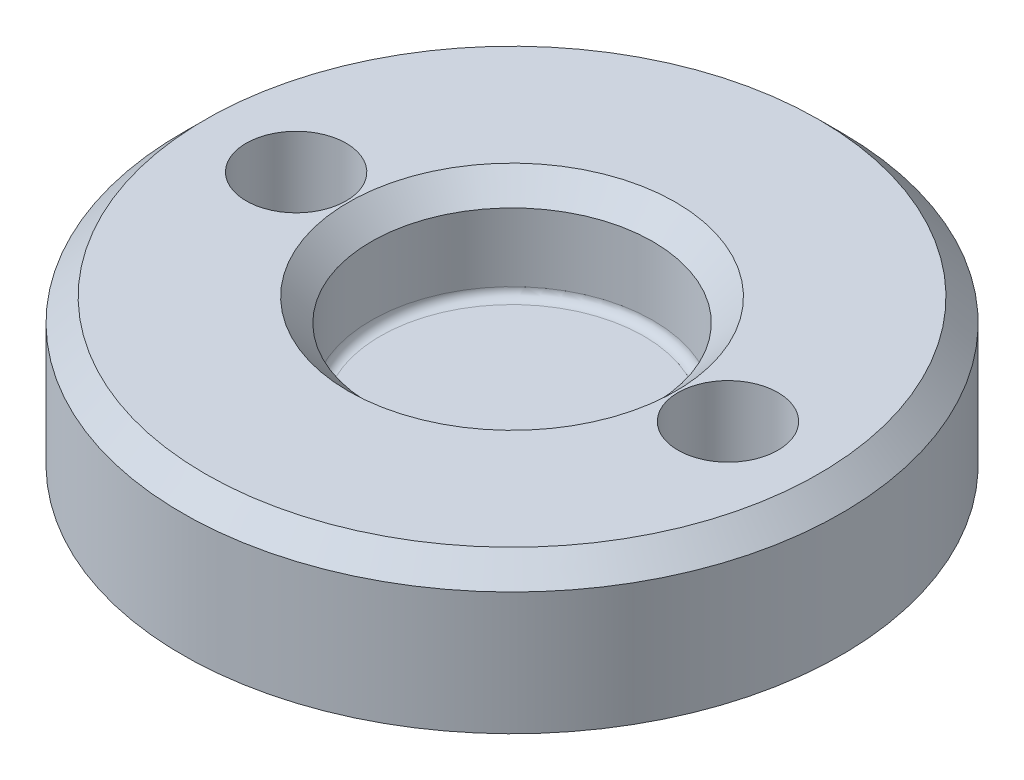
SolidWorks part; units mm, degrees
material "Brass"
ref_plane "Front Plane" through (0, 0, 0) normal (0, 0, 1) x (1, 0, 0)
ref_plane "Top Plane" through (0, 0, 0) normal (0, 1, 0) x (1, 0, 0)
ref_plane "Right Plane" through (0, 0, 0) normal (1, 0, 0) x (0, 0, -1)
sketch "Sketch1" plane through (0, 0, 0) normal (0, 0, 1) x (1, 0, 0)
  line L0 (0, 0) -> (0, 7.0462) construction
  line L1 (0, 0) -> (-7.25, 0)
  line L2 (-7.25, 0) -> (-7.25, 3.2)
  line L3 (-7.25, 3.2) -> (-3.1, 3.2)
  line L4 (-3.1, 3.2) -> (-3.1, 1)
  line L5 (-3.1, 1) -> (0, 1)
  line L6 (0, 0) -> (0, 1)
  dimension "D1" = 3.1
  dimension "D2" = 4.15
  dimension "D3" = 1
  dimension "D4" = 2.2
  dimension "D5" = 7.25
revolve "Revolve1" add sketch "Sketch1" angle 360 about L0
chamfer "Chamfer2" distance 0.5 angle 45 1 edges at (0, 3.2, -3.1)
sketch "Sketch2" plane through (0, 3.2, 0) normal (0, 1, 0) x (1, 0, 0)
  line L0 (-6.8053, -2.5) -> (-12.25, -2.5)
  line L1 (-12.25, -2.5) -> (-12.25, 2.5)
  line L2 (-12.25, 2.5) -> (-6.8053, 2.5)
  line L3 (-12.25, 0) -> (-7.25, 0) construction
  circle A0 centre (0, 0) radius 7.25 construction
  arc A1 (-6.8053, 2.5) -> (-6.8053, -2.5) centre (0, 0) ccw
  point P2 (-12.25, 0)
  dimension "D1" = 5
extrude "Boss-Extrude1" [suppressed] add sketch "Sketch2" against normal up to surface (3 mm away)
hole_wizard "CSK for M2 Flat Head Machine Screw1" positions "Sketch3" profile "Sketch4" countersink size "M2" standard "ANSI Metric"
sketch "Sketch3" plane through (0, 0, 0) normal (0, -1, 0) x (-1, 0, 0)
  point P0 (4.75, 0)
  dimension "D1" = 4.75
sketch "Sketch4" plane through (-4.75, 0, 0) normal (1, 0, 0) x (0, 0, -1)
  line L0 (0, 0) -> (0, 5.6609)
  line L1 (0, 5.6609) -> (1.1, 5)
  line L2 (1.1, 5) -> (1.1, 1.1)
  line L3 (1.1, 1.1) -> (2.2, 0)
  line L5 (2.2, 0) -> (0, 0)
  line L6 (-1.1, 1.1) -> (-2.2, 0) construction
  line L10 (0, 5.6609) -> (-1.1, 5) construction
  line L11 (0, -6.35) -> (0, 107.95) construction
  dimension "Hole Dia." = 2.2
  dimension "Hole Depth" = 5
  dimension "Near C'Sink Dia." = 4.4
  dimension "Near C'Sink Angle" = 90
  dimension "Drill Angle" = 118
sketch "Sketch5" [suppressed] plane through (0, 0, 0) normal (0, -1, 0) x (1, 0, 0)
  line L1 (-6.8053, 2.5) -> (-12.25, 2.5) construction
  line L2 (-6.8053, 2.5) -> (-12.25, 2.5) construction
  line L3 (-12.25, -2.5) -> (-6.8053, -2.5) construction
  line L4 (-4.75, -2.5) -> (-12.25, -2.5)
  line L5 (-12.25, -2.5) -> (-12.25, 2.5)
  line L9 (-12.25, 2.5) -> (-4.75, 2.5)
  arc A0 (-4.75, -2.5) -> (-4.75, 2.5) centre (-4.75, 0) cw
extrude "Cut-Extrude1" [suppressed] cut sketch "Sketch5" against normal through all both and the other way through all
pattern_circular "CirPattern1" count 2 over 360 about axis through (0, 0, 0) along (0, 1, 0) of "CSK for M2 Flat Head Machine Screw1", "Boss-Extrude1", "Cut-Extrude1"
fillet "Fillet1" [suppressed] radius 10
chamfer "Chamfer3" distance 0.5 angle 45 1 edges at (0, 3.2, -7.25)
fillet "Fillet2" radius 0.2 1 edges at (0, 1, -3.1)
